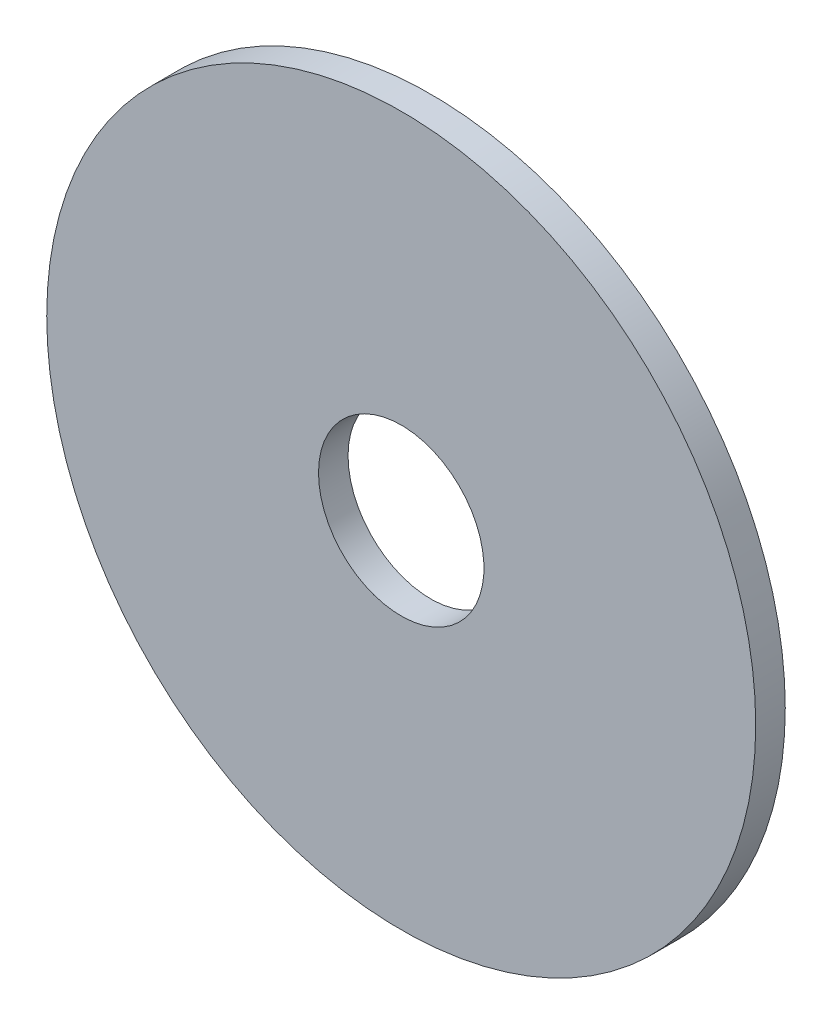
SolidWorks part; units mm, degrees
ref_plane "Front Plane" through (0, 0, 0) normal (0, 0, 1) x (1, 0, 0)
ref_plane "Top Plane" through (0, 0, 0) normal (0, 1, 0) x (1, 0, 0)
ref_plane "Right Plane" through (0, 0, 0) normal (1, 0, 0) x (0, 0, -1)
ref_plane "Plane1" through (0, 0, 0) normal (0, -1, 0) x (1, 0, 0)
sketch "Sketch1" plane through (0, 0, 0) normal (0, -1, 0) x (1, 0, 0)
  line L0 (18, 0) -> (18, 1.5)
  line L1 (18, 1.5) -> (4.2, 1.5)
  line L2 (4.2, 1.5) -> (4.2, 0)
  line L3 (4.2, 0) -> (18, 0)
  line L4 (0, 1.5) -> (0, 0) construction
revolve "Revolve1" add sketch "Sketch1" angle 360 about L4
